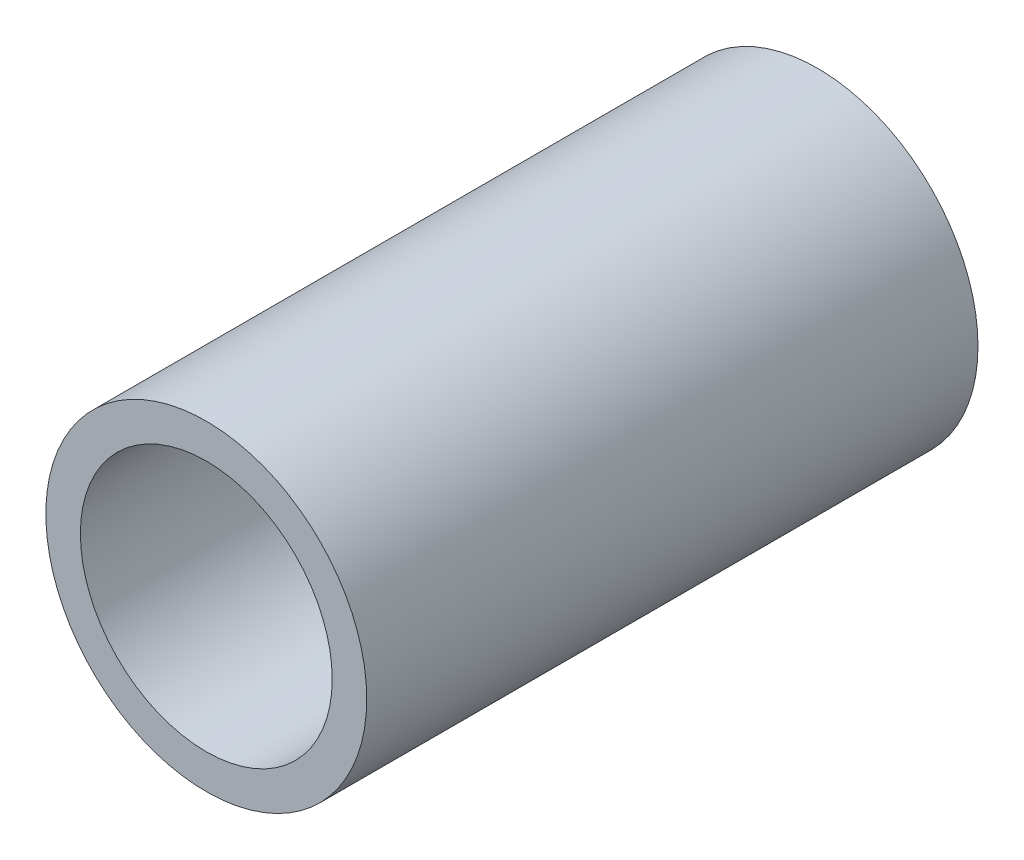
SolidWorks part; units mm, degrees
ref_plane "Front Plane" through (0, 0, 0) normal (0, 0, 1) x (1, 0, 0)
ref_plane "Top Plane" through (0, 0, 0) normal (0, 1, 0) x (1, 0, 0)
ref_plane "Right Plane" through (0, 0, 0) normal (1, 0, 0) x (0, 0, -1)
sketch "Sketch1" plane through (0, 0, 0) normal (0, 0, 1) x (1, 0, 0)
  circle A0 centre (0, 0) radius 10.4648
  circle A1 centre (0, 0) radius 13.335
  dimension "D1" = 2.8702
  dimension "D2" = 26.67
extrude "Boss-Extrude1" add sketch "Sketch1" along normal blind 50.8
